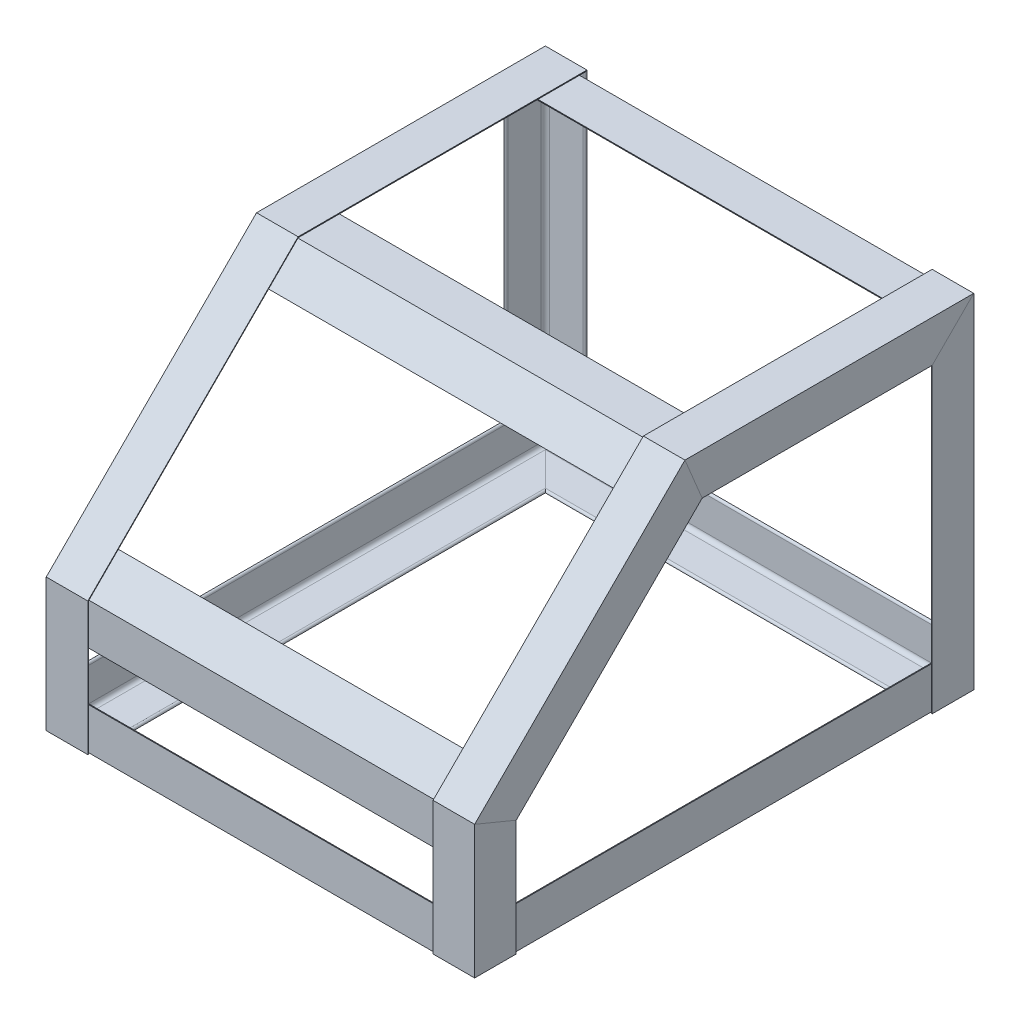
SolidWorks part; units mm, degrees
ref_plane "Front Plane" through (0, 0, 0) normal (0, 0, 1) x (1, 0, 0)
ref_plane "Top Plane" through (0, 0, 0) normal (0, 1, 0) x (1, 0, 0)
ref_plane "Right Plane" through (0, 0, 0) normal (1, 0, 0) x (0, 0, -1)
sketch3d "3DSketch1"
  line L0 (0, 0, 0) -> (0, 438.15, 0)
  line L1 (0, 438.15, 0) -> (641.35, 438.15, 0)
  line L2 (641.35, 438.15, 0) -> (641.35, 0, 0)
  line L3 (641.35, 0, 0) -> (0, 0, 0)
  line L4 (641.35, 0, 0) -> (641.35, 0, -749.3)
  line L5 (641.35, 0, -749.3) -> (0, 0, -749.3)
  line L6 (0, 0, -749.3) -> (0, 0, 0)
  line L7 (641.35, 0, -749.3) -> (641.35, 438.15, -749.3)
  line L8 (641.35, 438.15, -749.3) -> (641.35, 438.15, 0)
  line L9 (0, 438.15, 0) -> (0, 438.15, -749.3)
  line L10 (0, 438.15, -749.3) -> (0, 0, -749.3)
  line L11 (641.35, 438.15, -749.3) -> (0, 438.15, -749.3)
  dimension "D1" = 438.15
  dimension "D2" = 641.35
  dimension "D3" = 749.3
other "Ángulo de extremos redondeados al i AL L ANGLE RND END 2.5X2.5X0.125(1)"
ref_plane "Plane2" through (-3.175, -9.525, -749.3) normal (0, 0, 1) x (1, 0, 0)
sketch "Sketch1" plane through (-3.175, -9.525, -749.3) normal (0, 0, 1) x (1, 0, 0)
  line L0 (0, 0) -> (0, 63.5)
  line L1 (0, 63.5) -> (0.0051, 63.5)
  line L2 (3.175, 60.3301) -> (3.175, 9.525)
  line L3 (9.525, 3.175) -> (60.3301, 3.175)
  line L4 (63.5, 0.0051) -> (63.5, 0)
  line L5 (63.5, 0) -> (0, 0)
  arc A0 (63.5, 0.0051) -> (60.3301, 3.175) centre (60.3301, 0.0051) ccw
  arc A1 (0.0051, 63.5) -> (3.175, 60.3301) centre (0.0051, 60.3301) cw
  arc A2 (9.525, 3.175) -> (3.175, 9.525) centre (9.525, 9.525) cw
  circle A3 centre (0, 0) radius 3.175 construction
  point P10 (0, 31.75)
  point P14 (31.75, 0)
  point P15 (0, 0)
  dimension "D2" = 0.0051
  dimension "Radius_1" = 6.35
  dimension "Radius_2" = 3.175
  dimension "D1" = 3.175
  dimension "V_leg" = 63.5
  dimension "H_leg" = 63.5
  dimension "Thickness" = 3.175
  dimension "Flat_wid" = 0.0051
ref_plane "Plano2" through (320.675, 0, 0) normal (1, 0, 0) x (0, 0, -1)
sketch3d "Croquis3D1"
  line L10 (644.5199, 53.975, -374.65) -> (-3.1699, 53.975, -374.65) construction
  line L11 (644.5199, 53.975, -752.4699) -> (644.5199, 53.975, 3.1699) construction
  line L12 (-3.1699, 53.975, 3.1699) -> (-3.1699, 53.975, -752.4699) construction
  line L13 (320.675, 53.975, -374.65) -> (320.675, 53.975, -752.4699) construction
  line L14 (-3.1699, 53.975, -752.4699) -> (644.5199, 53.975, -752.4699) construction
  line L18 (644.525, -9.525, -752.475) -> (644.525, -9.525, 3.175) construction
  line L19 (644.525, -9.525, -752.475) -> (644.525, -9.525, -755.65) construction
  line L20 (644.525, -9.525, -752.475) -> (647.7, -9.525, -752.475) construction
  line L21 (647.7, -9.525, -752.475) -> (647.7, -9.525, -755.65) construction
  line L22 (644.525, -9.525, -755.65) -> (647.7, -9.525, -755.65) construction
  line L23 (647.7, -9.525, -755.65) -> (647.7, -9.525, 6.35) construction
  line L24 (644.525, -9.525, 3.175) -> (644.525, -9.525, 6.35) construction
  line L25 (644.525, -9.525, 3.175) -> (647.7, -9.525, 3.175) construction
  line L26 (647.7, -9.525, 3.175) -> (647.7, -9.525, 6.35) construction
  line L27 (644.525, -9.525, 6.35) -> (647.7, -9.525, 6.35) construction
  line L28 (647.7, -9.525, 6.35) -> (647.7, 193.675, 6.35)
  line L29 (647.7, -9.525, -755.65) -> (647.7, 514.731, -755.65)
  line L30 (647.7, 193.675, 6.35) -> (647.7, 523.875, 6.35) construction
  line L31 (-6.35, 514.731, -752.475) -> (-6.35, 511.556, -752.475) construction
  line L32 (647.7, 193.675, 6.35) -> (647.7, 514.731, -314.706)
  line L33 (647.7, 514.731, -314.706) -> (647.7, 514.731, -755.65)
  line L34 (647.7, 193.675, 6.35) -> (647.7, 193.675, -755.65) construction
  line L35 (-6.35, -9.525, 6.35) -> (-6.35, 193.675, 6.35)
  line L36 (-6.35, 193.675, 6.35) -> (-6.35, 514.731, -314.706)
  line L37 (-6.35, -9.525, -755.65) -> (-6.35, 514.731, -755.65)
  line L38 (-6.35, 514.731, -314.706) -> (-6.35, 514.731, -755.65)
  line L39 (-6.35, 511.556, -752.475) -> (-6.35, 511.556, -755.65) construction
  line L40 (-6.35, 511.556, -752.475) -> (-3.175, 511.556, -752.475) construction
  line L41 (-3.175, 511.556, -752.475) -> (644.525, 511.556, -752.475)
  line L42 (647.7, 514.731, -752.475) -> (647.7, 511.556, -752.475) construction
  line L43 (647.7, 511.556, -752.475) -> (647.7, 511.556, -755.65) construction
  line L44 (647.7, 511.556, -752.475) -> (644.525, 511.556, -752.475) construction
  line L45 (-6.35, 193.675, 6.35) -> (-3.175, 193.675, 6.35) construction
  line L46 (-3.175, 193.675, 6.35) -> (-3.175, 193.675, 3.175) construction
  line L47 (-3.175, 193.675, 3.175) -> (-6.35, 193.675, 3.175) construction
  line L48 (-6.35, 193.675, 3.175) -> (-6.35, 193.675, 6.35) construction
  line L49 (647.7, 193.675, 6.35) -> (644.5047, 193.675, 6.35) construction
  line L50 (644.5047, 193.675, 6.35) -> (644.5047, 193.675, 3.175) construction
  line L51 (644.5047, 193.675, 3.175) -> (647.7, 193.675, 3.175) construction
  line L52 (644.5047, 193.675, 3.175) -> (-3.175, 193.675, 3.175)
  line L53 (-6.35, 514.731, -314.706) -> (-6.35, 511.556, -314.706) construction
  line L54 (-6.35, 511.556, -314.706) -> (-6.35, 511.556, -317.881) construction
  line L55 (-6.35, 511.556, -317.881) -> (-6.35, 514.731, -317.881) construction
  line L56 (-6.35, 511.556, -314.706) -> (644.525, 511.556, -314.706) construction
  line L57 (647.7, 514.731, -314.706) -> (647.7, 511.556, -314.706) construction
  dimension "D1" = 3.175
  dimension "D3" = 3.175
  dimension "D2" = 3.175
  dimension "D4" = 3.175
  dimension "D5" = 203.2
  dimension "D7" = 3.175
  dimension "D6" = 524.256
  dimension "D9" = 3.175
  dimension "D8" = 45
  dimension "D10" = 3.175
  dimension "D11" = 3.175
  dimension "D12" = 3.175
  dimension "D13" = 3.175
  dimension "D14" = 3.175
  dimension "D15" = 3.175
  dimension "D16" = 3.1953
  dimension "D17" = 3.175
  dimension "D18" = 3.175
  dimension "D19" = 3.175
  dimension "D20" = 3.175
  dimension "D21" = 3.175
  dimension "D22" = 440.944
  dimension "D23" = 454.0417
  dimension "D24" = 135
other "Ángulo de extremos redondeados al i AL L ANGLE RND END 2.5X2.5X0.125(3)"
ref_plane "Plano3" through (647.7, -9.525, 6.35) normal (0, -1, 0) x (-1, 0, 0)
sketch "Sketch12" plane through (647.7, -9.525, 6.35) normal (0, -1, 0) x (-1, 0, 0)
  line L0 (0, 0) -> (0, 63.5)
  line L1 (0, 63.5) -> (0.0051, 63.5)
  line L2 (3.175, 60.3301) -> (3.175, 9.525)
  line L3 (9.525, 3.175) -> (60.3301, 3.175)
  line L4 (63.5, 0.0051) -> (63.5, 0)
  line L5 (63.5, 0) -> (0, 0)
  arc A0 (63.5, 0.0051) -> (60.3301, 3.175) centre (60.3301, 0.0051) ccw
  arc A1 (0.0051, 63.5) -> (3.175, 60.3301) centre (0.0051, 60.3301) cw
  arc A2 (9.525, 3.175) -> (3.175, 9.525) centre (9.525, 9.525) cw
  circle A3 centre (0, 0) radius 3.175 construction
  point P10 (0, 31.75)
  point P14 (31.75, 0)
  point P15 (0, 0)
  dimension "D2" = 0.0051
  dimension "Radius_1" = 6.35
  dimension "Radius_2" = 3.175
  dimension "D1" = 3.175
  dimension "V_leg" = 63.5
  dimension "H_leg" = 63.5
  dimension "Thickness" = 3.175
  dimension "Flat_wid" = 0.0051
other "Ángulo de extremos redondeados al i AL L ANGLE RND END 2.5X2.5X0.125(21)"
ref_plane "Plano8" through (-6.35, -9.525, 6.35) normal (0, 1, 0) x (1, 0, 0)
sketch "Sketch17" plane through (-6.35, -9.525, 6.35) normal (0, 1, 0) x (1, 0, 0)
  line L0 (0, 0) -> (0, 63.5)
  line L1 (0, 63.5) -> (0.0051, 63.5)
  line L2 (3.175, 60.3301) -> (3.175, 9.525)
  line L3 (9.525, 3.175) -> (60.3301, 3.175)
  line L4 (63.5, 0.0051) -> (63.5, 0)
  line L5 (63.5, 0) -> (0, 0)
  arc A0 (63.5, 0.0051) -> (60.3301, 3.175) centre (60.3301, 0.0051) ccw
  arc A1 (0.0051, 63.5) -> (3.175, 60.3301) centre (0.0051, 60.3301) cw
  arc A2 (9.525, 3.175) -> (3.175, 9.525) centre (9.525, 9.525) cw
  circle A3 centre (0, 0) radius 3.175 construction
  point P10 (0, 31.75)
  point P14 (31.75, 0)
  point P15 (0, 0)
  dimension "D2" = 0.0051
  dimension "Radius_1" = 6.35
  dimension "Radius_2" = 3.175
  dimension "D1" = 3.175
  dimension "V_leg" = 63.5
  dimension "H_leg" = 63.5
  dimension "Thickness" = 3.175
  dimension "Flat_wid" = 0.0051
sketch "Croquis2" plane through (-3.175, 0, 0) normal (1, 0, 0) x (0, 0, -1)
  line L0 (-3.175, 192.3599) -> (-3.175, 128.8599)
  line L1 (-3.175, 192.3599) -> (-3.175, -9.525) construction
  line L2 (-3.175, 128.8599) -> (1.5875, 128.8599)
  line L3 (1.5875, 128.8599) -> (1.5875, 190.3872)
  line L4 (3.175, 189.7296) -> (-3.175, 192.3599) construction
  line L5 (-3.175, 192.3599) -> (1.5875, 190.3872) construction
  line L6 (45.0939, 233.8936) -> (1.5875, 190.3872)
  line L7 (41.7263, 237.2612) -> (45.0939, 233.8936)
  line L8 (-3.175, 192.3599) -> (41.7263, 237.2612)
  line L9 (316.0211, 511.556) -> (379.5211, 511.556)
  line L10 (752.475, 511.556) -> (316.0211, 511.556) construction
  line L11 (379.5211, 511.556) -> (379.5211, 506.7935)
  line L12 (379.5211, 506.7935) -> (317.9938, 506.7935)
  line L13 (316.0211, 511.556) -> (318.6514, 505.206) construction
  line L14 (317.9938, 506.7935) -> (316.0211, 511.556) construction
  line L15 (316.0211, 511.556) -> (317.9938, 506.7935) construction
  line L16 (274.4874, 463.2871) -> (317.9938, 506.7935)
  line L17 (271.1198, 466.6547) -> (274.4874, 463.2871)
  line L18 (316.0211, 511.556) -> (271.1198, 466.6547)
  dimension "D1" = 4.7625
  dimension "D2" = 63.5
  dimension "D3" = 4.7625
  dimension "D4" = 63.5
extrude "Saliente-Extruir1" add sketch "Croquis2" along normal up to surface (647.7 mm away) separate body up to face at (644.525, 329.5055, -178.8755)
sketch3d "Croquis3D5"
  line L0 (638.175, 511.556, -752.475) -> (644.525, 505.206, -746.125) construction
  line L1 (-3.175, 505.206, -746.125) -> (3.175, 511.556, -752.475) construction
  line L2 (0, 508.381, -749.3) -> (641.35, 508.381, -749.3)
other "Ángulo de extremos redondeados al i AL L ANGLE RND END 2.5X2.5X0.125(26)"
ref_plane "Plano11" through (0, 508.381, -749.3) normal (-1, 0, 0) x (0, -1, 0)
sketch "Sketch110" plane through (0, 508.381, -749.3) normal (-1, 0, 0) x (0, -1, 0)
  line L0 (0, 0) -> (0, 63.5)
  line L1 (0, 63.5) -> (0.0051, 63.5)
  line L2 (3.175, 60.3301) -> (3.175, 9.525)
  line L3 (9.525, 3.175) -> (60.3301, 3.175)
  line L4 (63.5, 0.0051) -> (63.5, 0)
  line L5 (63.5, 0) -> (0, 0)
  arc A0 (63.5, 0.0051) -> (60.3301, 3.175) centre (60.3301, 0.0051) ccw
  arc A1 (0.0051, 63.5) -> (3.175, 60.3301) centre (0.0051, 60.3301) cw
  arc A2 (9.525, 3.175) -> (3.175, 9.525) centre (9.525, 9.525) cw
  circle A3 centre (0, 0) radius 3.175 construction
  point P10 (0, 31.75)
  point P14 (31.75, 0)
  point P15 (0, 0)
  dimension "D2" = 0.0051
  dimension "Radius_1" = 6.35
  dimension "Radius_2" = 3.175
  dimension "D1" = 3.175
  dimension "V_leg" = 63.5
  dimension "H_leg" = 63.5
  dimension "Thickness" = 3.175
  dimension "Flat_wid" = 0.0051
sketch "Croquis4" plane through (647.7, 0, 0) normal (1, 0, 0) x (0, 0, -1)
  line L1 (57.15, 167.3724) -> (-67.4689, 42.7535)
  line L2 (341.0086, 451.231) -> (57.15, 167.3724) construction
  line L3 (-6.35, 193.675) -> (-97.3961, 102.6289)
  line L4 (314.706, 514.731) -> (-6.35, 193.675) construction
  line L5 (38.5513, 148.7737) -> (-6.35, 193.675)
  line L6 (341.0086, 451.231) -> (442.2237, 552.4462)
  line L7 (314.706, 514.731) -> (359.6073, 469.8297)
  line L8 (-6.35, 193.675) -> (83.4526, 193.675)
  line L9 (692.15, 451.231) -> (692.15, 514.731)
  line L10 (755.65, 514.731) -> (314.706, 514.731) construction
  line L11 (692.15, 514.731) -> (755.65, 514.731)
  line L12 (755.65, 514.731) -> (692.15, 451.231)
  dimension "D1" = 63.5
  dimension "D2" = 26.3026
  dimension "D3" = 45
  dimension "D4" = 63.5
